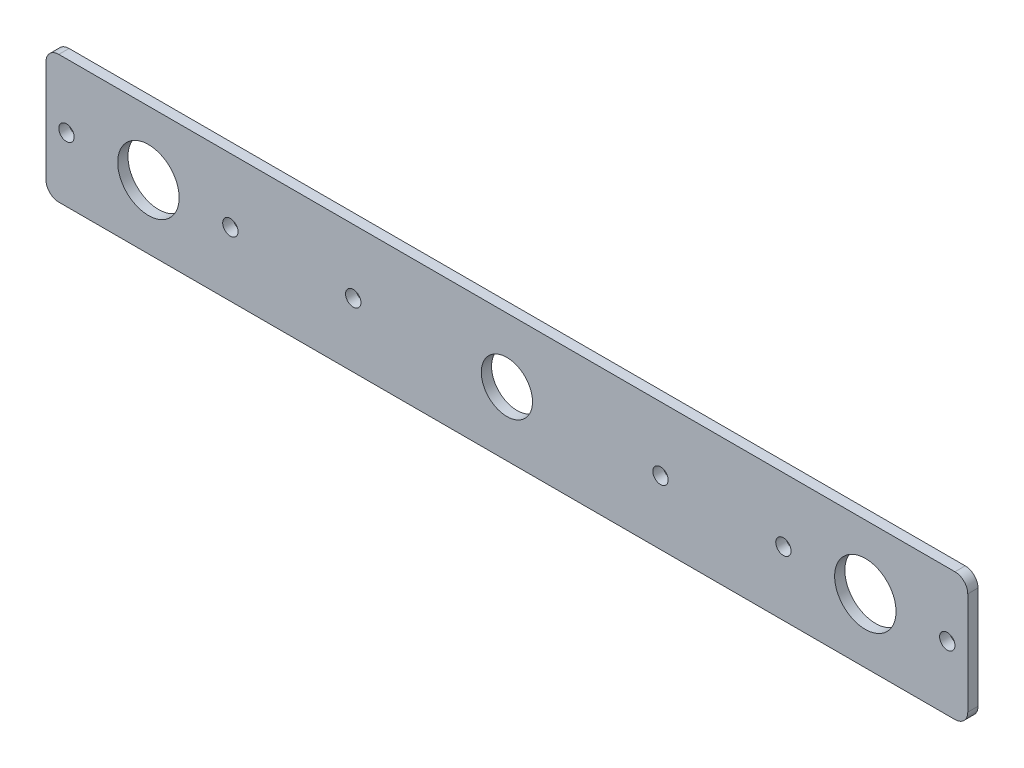
SolidWorks part; units mm, degrees
ref_plane "Front Plane" through (0, 0, 0) normal (0, 0, 1) x (1, 0, 0)
ref_plane "Top Plane" through (0, 0, 0) normal (0, 1, 0) x (1, 0, 0)
ref_plane "Right Plane" through (0, 0, 0) normal (1, 0, 0) x (0, 0, -1)
sketch "Model" plane through (0, 0, 0) normal (0, 0, 1) x (1, 0, 0)
  line L0 (0, 0) -> (0, 25) construction
  line L1 (-87.5, 25) -> (87.5, 25)
  line L2 (-90, 22.5) -> (-90, 2.5)
  line L3 (-87.5, 0) -> (87.5, 0)
  line L4 (90, 22.5) -> (90, 2.5)
  line L5 (-90, 12.5) -> (90, 12.5) construction
  line L6 (-70, 12.5) -> (-70, 25) construction
  arc A0 (-87.5, 25) -> (-90, 22.5) centre (-87.5, 22.5) ccw
  arc A1 (-90, 2.5) -> (-87.5, 0) centre (-87.5, 2.5) ccw
  arc A2 (87.5, 0) -> (90, 2.5) centre (87.5, 2.5) ccw
  arc A3 (90, 22.5) -> (87.5, 25) centre (87.5, 22.5) ccw
  circle A4 centre (86, 12.5) radius 1.5
  circle A5 centre (-86, 12.5) radius 1.5
  circle A6 centre (0, 12.5) radius 5
  circle A7 centre (-70, 12.5) radius 6
  circle A8 centre (70, 12.5) radius 6
  circle A9 centre (-54, 12.5) radius 1.5
  circle A10 centre (54, 12.5) radius 1.5
  circle A11 centre (-30, 12.5) radius 1.5
  circle A12 centre (30, 12.5) radius 1.5
  dimension "D1" = 5
  dimension "D4" = 3
  dimension "D5" = 10
  dimension "D8" = 12
  dimension "D2" = 25
  dimension "D3" = 180
  dimension "D7" = 70
  dimension "D6" = 16
  dimension "D9" = 30
extrude "Boss-Extrude1" add sketch "Model" along normal blind 2
equation "\"acrylic-thickness\" = 2mm"
equation "\"linear-thread-nut-dia\" = 12.8mm ' Outer Diameter of the Nut used on the X Axis, typically M8 = 10mm"
equation "\"linear-bar-dia\" = 8mm ' Diameter of the metal slide bar used on the X Axis"
equation "\"linear-thread-dia\" = 8mm ' Diameter of the metal threaded rod used on the X Axis"
equation "\"linear-bar-bearingouter-dia\" = 15mm ' Diameter of the outer side of the bearing"
equation "\"D1@Boss-Extrude1\" = \"acrylic-thickness\""
equation "\"D5@Model\"=\"linear-thread-dia\" +2"
equation "\"D8@Model\"=\"linear-bar-bearingouter-dia\" - 3"
